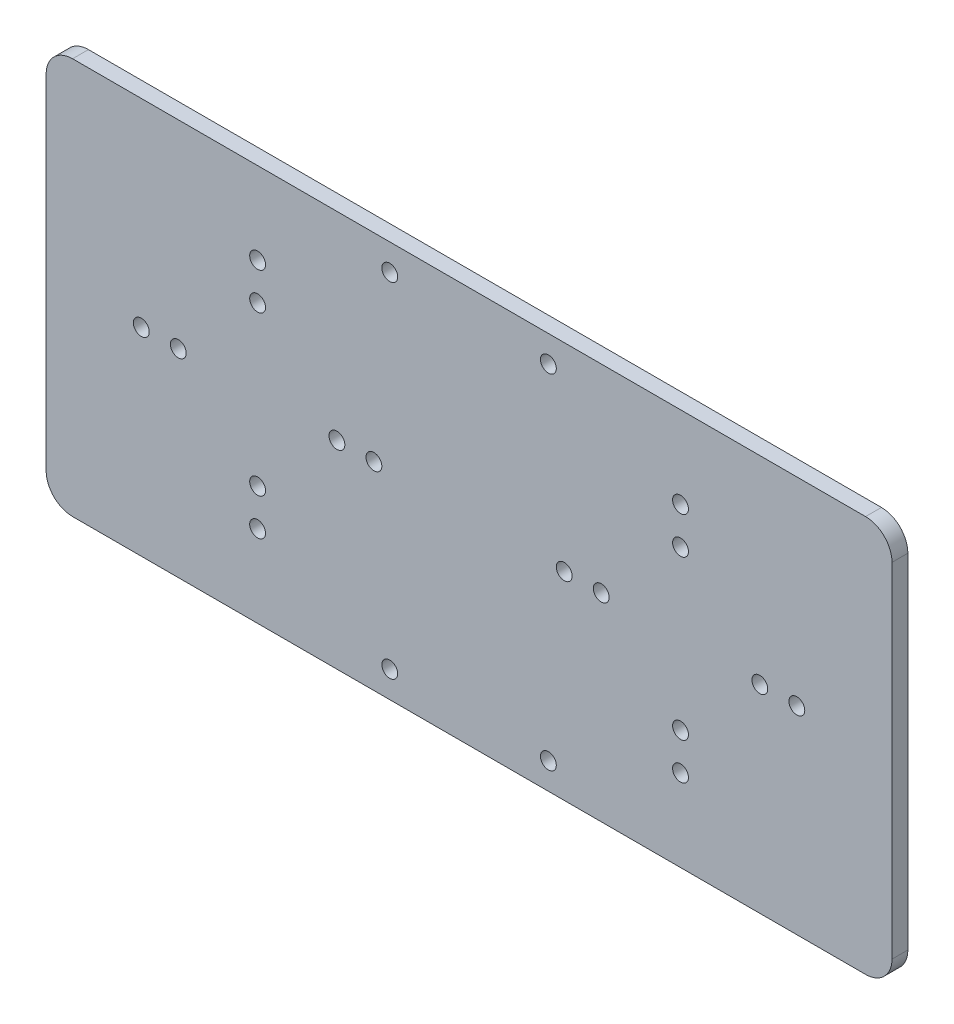
SolidWorks part; units mm, degrees
ref_plane "前视基准面" through (0, 0, 0) normal (0, 0, 1) x (1, 0, 0)
ref_plane "上视基准面" through (0, 0, 0) normal (0, 1, 0) x (1, 0, 0)
ref_plane "右视基准面" through (0, 0, 0) normal (1, 0, 0) x (0, 0, -1)
sketch "草图1" plane through (0, 0, 0) normal (0, 0, 1) x (1, 0, 0)
  line L1 (0, 0) -> (160, 0)
  line L2 (0, 0) -> (0, -75)
  line L3 (0, -75) -> (160, -75)
  line L4 (160, 0) -> (160, -75)
  dimension "D1" = 160
  dimension "D2" = 75
extrude "凸台-拉伸1" add sketch "草图1" along normal blind 3
sketch "草图2" plane through (0, 0, 3) normal (0, 0, 1) x (1, 0, 0)
  line L0 (0, -75) -> (160, -75) construction
  line L1 (0, 0) -> (0, -75) construction
  line L2 (160, -75) -> (160, 0) construction
  circle A0 centre (40, -37.5) radius 34
  circle A1 centre (120, -37.5) radius 34
  dimension "D1" = 37.5
  dimension "D3" = 37.5
  dimension "D4" = 40
  dimension "D2" = 40
sketch "草图3" plane through (0, 0, 3) normal (0, 0, 1) x (1, 0, 0)
sketch "草图4" plane through (0, 0, 3) normal (0, 0, 1) x (1, 0, 0)
  circle A1 centre (40, -15.5) radius 1.5
  circle A2 centre (18, -37.5) radius 1.5
  circle A3 centre (62, -37.5) radius 1.5
  circle A4 centre (40, -59.5) radius 1.5
  circle A6 centre (40, -22.5) radius 1.5
  circle A7 centre (25, -37.5) radius 1.5
  circle A8 centre (55, -37.5) radius 1.5
  circle A9 centre (40, -52.5) radius 1.5
extrude "切除-拉伸1" cut sketch "草图4" against normal blind 3
sketch "草图5" plane through (0, 0, 3) normal (0, 0, 1) x (1, 0, 0)
  circle A2 centre (120, -15.5) radius 1.5
  circle A3 centre (98, -37.5) radius 1.5
  circle A4 centre (120, -59.5) radius 1.5
  circle A5 centre (142, -37.5) radius 1.5
  circle A6 centre (120, -22.5) radius 1.5
  circle A7 centre (105, -37.5) radius 1.5
  circle A8 centre (120, -52.5) radius 1.5
  circle A9 centre (135, -37.5) radius 1.5
extrude "切除-拉伸2" cut sketch "草图5" against normal blind 3
sketch "草图6" plane through (0, 0, 3) normal (0, 0, 1) x (1, 0, 0)
  line L0 (160, 0) -> (0, 0) construction
  line L1 (0, -75) -> (160, -75) construction
  line L2 (0, 0) -> (0, -75) construction
  circle A0 centre (65, -5) radius 1.5
  circle A1 centre (95, -5) radius 1.5
  circle A2 centre (65, -70) radius 1.5
  circle A3 centre (95, -70) radius 1.5
  dimension "D1" = 5
  dimension "D2" = 3
  dimension "D3" = 5
  dimension "D4" = 5
  dimension "D5" = 5
  dimension "D6" = 30
  dimension "D7" = 65
  dimension "D8" = 65
  dimension "D9" = 30
extrude "切除-拉伸3" cut sketch "草图6" against normal blind 3
fillet "圆角1" radius 5 1 edges at (160, 0, 1.5)
fillet "圆角2" radius 5 1 edges at (0, 0, 1.5)
fillet "圆角3" radius 5 1 edges at (0, -75, 1.5)
fillet "圆角4" radius 5 1 edges at (160, -75, 1.5)
